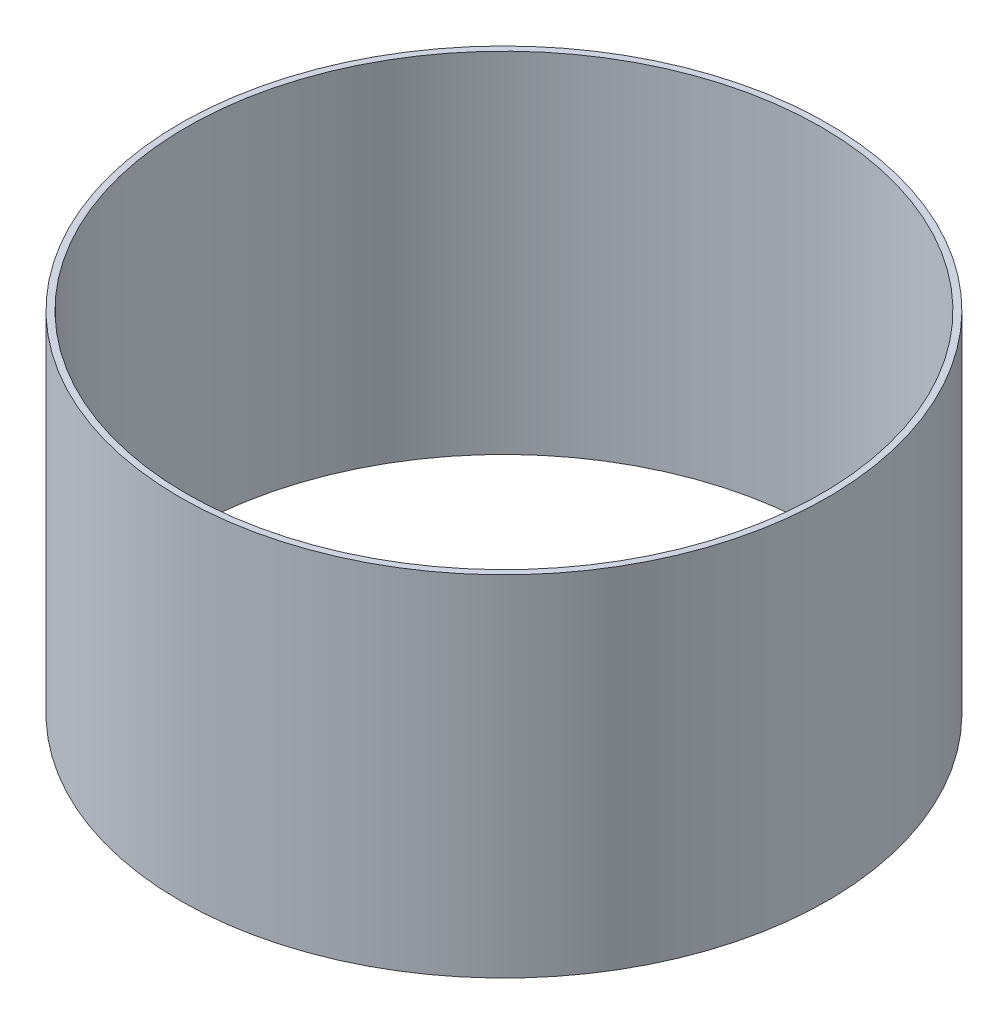
SolidWorks part; units mm, degrees
ref_plane "Front Plane" through (0, 0, 0) normal (0, 0, 1) x (1, 0, 0)
ref_plane "Top Plane" through (0, 0, 0) normal (0, 1, 0) x (1, 0, 0)
ref_plane "Right Plane" through (0, 0, 0) normal (1, 0, 0) x (0, 0, -1)
sketch "Sketch1" plane through (0, 0, 0) normal (0, 1, 0) x (1, 0, 0)
  circle A0 centre (0, 0) radius 51
  circle A1 centre (0, 0) radius 50
  dimension "D1" = 102
  dimension "D2" = 100
extrude "Boss-Extrude1" add sketch "Sketch1" along normal blind 55
